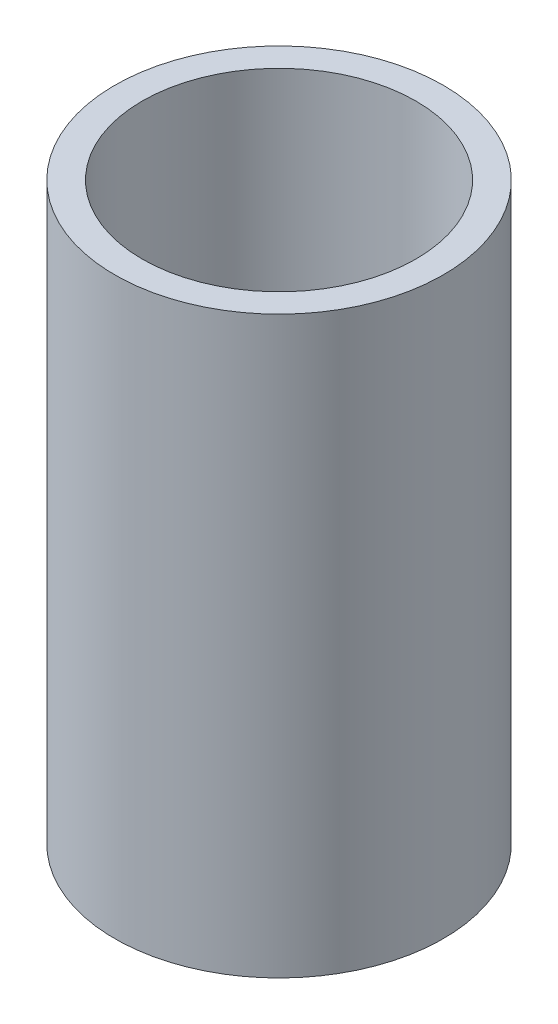
SolidWorks part; units mm, degrees
material "Hexcel AS4C (3000 丝)"
ref_plane "前视基准面" through (0, 0, 0) normal (0, 0, 1) x (1, 0, 0)
ref_plane "上视基准面" through (0, 0, 0) normal (0, 1, 0) x (1, 0, 0)
ref_plane "右视基准面" through (0, 0, 0) normal (1, 0, 0) x (0, 0, -1)
sketch "草图1" plane through (0, 0, 0) normal (0, 1, 0) x (1, 0, 0)
  circle A0 centre (0, 0) radius 6
  circle A1 centre (0, 0) radius 5
  dimension "D1" = 10
  dimension "D2" = 12
extrude "凸台-拉伸1" add sketch "草图1" along normal blind 21
